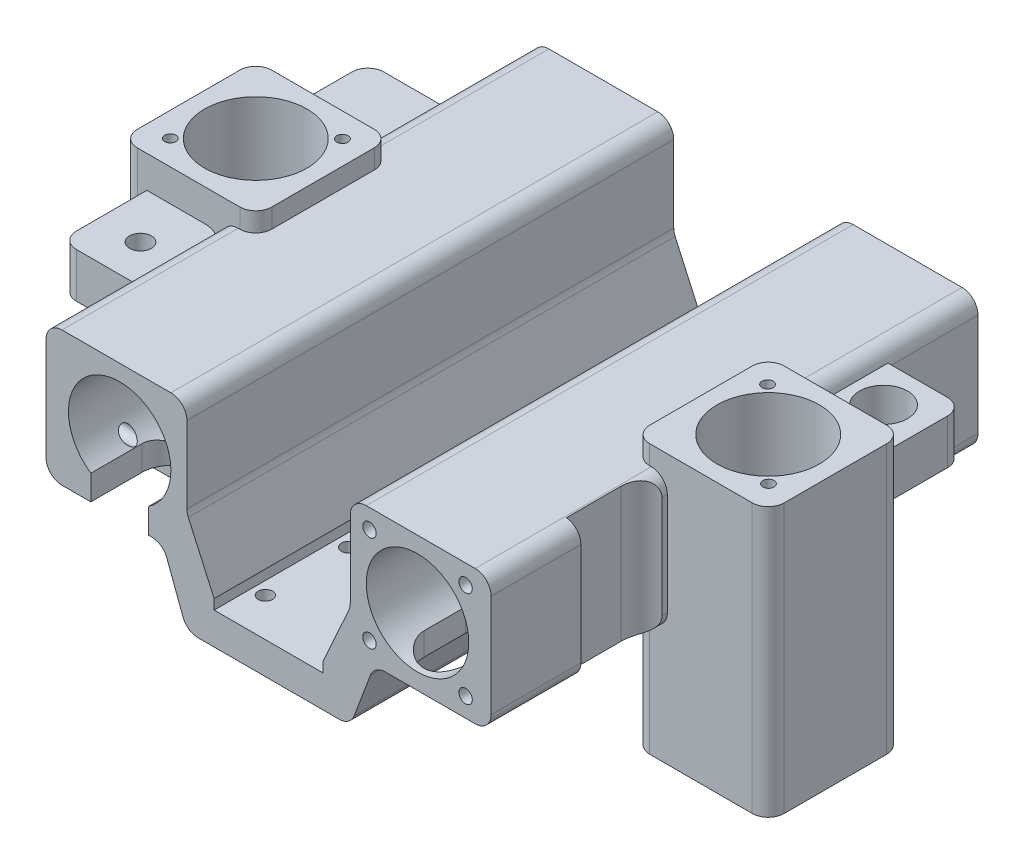
SolidWorks part; units mm, degrees
ref_plane "前视基准面" through (0, 0, 0) normal (0, 0, 1) x (1, 0, 0)
ref_plane "上视基准面" through (0, 0, 0) normal (0, 1, 0) x (1, 0, 0)
ref_plane "右视基准面" through (0, 0, 0) normal (1, 0, 0) x (0, 0, -1)
sketch "草图1" plane through (0, 0, 0) normal (0, 0, 1) x (1, 0, 0)
  line L453 (2723.1468, 1081.2034) -> (2758.5766, 1081.2034) construction
  line L454 (2741.2781, 1063.9052) -> (2741.2781, 1099.5334) construction
  line L455 (2648.2781, 1065.0579) -> (2648.2781, 1099.5334) construction
  line L456 (2631.7099, 1081.2034) -> (2665.5766, 1081.2034) construction
  line L472 (2731.2431, 1060.2034) -> (2759.2781, 1060.2034)
  line L473 (2725.2781, 1102.2034) -> (2759.2781, 1102.2034)
  line L474 (2669.2781, 1073.2765) -> (2669.2781, 1097.2034)
  line L475 (2720.2781, 1073.2765) -> (2720.2781, 1097.2034)
  line L476 (2677.7781, 1053.3145) -> (2669.7185, 1071.2247)
  line L477 (2711.7781, 1053.3145) -> (2719.8377, 1071.2247)
  line L478 (2721.4948, 1043.4478) -> (2726.5615, 1056.959)
  line L479 (2668.0615, 1043.4478) -> (2662.9948, 1056.959)
  line L480 (2694.7781, 1009.1509) -> (2694.7781, 1126.7648) construction
  line L483 (2764.2781, 1065.2034) -> (2764.2781, 1097.2034)
  line L484 (2625.2781, 1065.2034) -> (2625.2781, 1097.2034)
  line L485 (2677.7781, 1050.2034) -> (2711.7781, 1050.2034)
  line L486 (2711.7781, 1050.2034) -> (2711.7781, 1053.3145)
  line L487 (2677.7781, 1050.2034) -> (2677.7781, 1053.3145)
  line L488 (2672.7431, 1040.2034) -> (2716.8131, 1040.2034)
  line L491 (2630.2781, 1060.2034) -> (2658.3131, 1060.2034)
  line L492 (2630.2781, 1102.2034) -> (2664.2781, 1102.2034)
  circle A141 centre (2648.2781, 1081.2034) radius 14
  circle A142 centre (2741.2781, 1081.2034) radius 16
  arc A143 (2759.2781, 1060.2034) -> (2764.2781, 1065.2034) centre (2759.2781, 1065.2034) ccw
  arc A144 (2731.2431, 1060.2034) -> (2726.5615, 1056.959) centre (2731.2431, 1055.2034) ccw
  arc A145 (2764.2781, 1097.2034) -> (2759.2781, 1102.2034) centre (2759.2781, 1097.2034) ccw
  arc A146 (2725.2781, 1102.2034) -> (2720.2781, 1097.2034) centre (2725.2781, 1097.2034) ccw
  arc A147 (2669.2781, 1073.2765) -> (2669.7185, 1071.2247) centre (2674.2781, 1073.2765) ccw
  arc A148 (2719.8377, 1071.2247) -> (2720.2781, 1073.2765) centre (2715.2781, 1073.2765) ccw
  arc A149 (2716.8131, 1040.2034) -> (2721.4948, 1043.4478) centre (2716.8131, 1045.2034) ccw
  arc A150 (2668.0615, 1043.4478) -> (2672.7431, 1040.2034) centre (2672.7431, 1045.2034) ccw
  arc A151 (2625.2781, 1065.2034) -> (2630.2781, 1060.2034) centre (2630.2781, 1065.2034) ccw
  arc A152 (2662.9948, 1056.959) -> (2658.3131, 1060.2034) centre (2658.3131, 1055.2034) ccw
  arc A153 (2630.2781, 1102.2034) -> (2625.2781, 1097.2034) centre (2630.2781, 1097.2034) ccw
  arc A154 (2669.2781, 1097.2034) -> (2664.2781, 1102.2034) centre (2664.2781, 1097.2034) ccw
extrude "拉伸1" add sketch "草图1" along normal blind 152
ref_plane "基准面2" through (0, 1108.2034, 0) normal (0, 1, 0) x (-1, 0, 0)
sketch "草图3" plane through (0, 1108.2034, 0) normal (0, 1, 0) x (-1, 0, 0)
  line L0 (-2694.7781, 0) -> (-2694.7781, 152) construction
  line L1 (-2598.7781, 55) -> (-2630.7781, 55)
  line L2 (-2593.7781, 60) -> (-2593.7781, 92)
  line L3 (-2598.7781, 97) -> (-2630.7781, 97)
  line L4 (-2635.7781, 60) -> (-2635.7781, 92)
  line L5 (-2711.7781, 0) -> (-2677.7781, 0) construction
  line L6 (-2711.7781, 152) -> (-2677.7781, 152) construction
  line L7 (-2664.2781, 0) -> (-2630.2781, 0) construction
  line L8 (-2790.7781, 97) -> (-2758.7781, 97)
  line L9 (-2753.7781, 60) -> (-2753.7781, 92)
  line L10 (-2790.7781, 55) -> (-2758.7781, 55)
  line L11 (-2795.7781, 60) -> (-2795.7781, 92)
  arc A0 (-2593.7781, 60) -> (-2598.7781, 55) centre (-2598.7781, 60) cw
  arc A1 (-2635.7781, 60) -> (-2630.7781, 55) centre (-2630.7781, 60) ccw
  arc A2 (-2598.7781, 97) -> (-2593.7781, 92) centre (-2598.7781, 92) cw
  arc A3 (-2635.7781, 92) -> (-2630.7781, 97) centre (-2630.7781, 92) cw
  circle A4 centre (-2614.7781, 76) radius 16
  arc A5 (-2790.7781, 97) -> (-2795.7781, 92) centre (-2790.7781, 92) ccw
  arc A6 (-2753.7781, 92) -> (-2758.7781, 97) centre (-2758.7781, 92) ccw
  arc A7 (-2753.7781, 60) -> (-2758.7781, 55) centre (-2758.7781, 60) cw
  circle A8 centre (-2774.7781, 76) radius 16
  arc A9 (-2795.7781, 60) -> (-2790.7781, 55) centre (-2790.7781, 60) ccw
  point P6 (-2593.7781, 55)
  point P9 (-2635.7781, 55)
  point P12 (-2593.7781, 97)
  dimension "D3" = 5
  dimension "D6" = 32
  dimension "D7" = 21
  dimension "D8" = 21
  dimension "D1" = 42
  dimension "D2" = 42
  dimension "D4" = 59
  dimension "D5" = 55
extrude "拉伸2" add sketch "草图3" against normal blind 84
sketch "草图4" plane through (0, 1108.2034, 0) normal (0, 1, 0) x (-1, 0, 0)
  line L0 (-2694.7781, 0) -> (-1335.5398, -1233.902) construction
  line L1 (-2711.7781, 0) -> (-2677.7781, 0) construction
  line L2 (-2694.7781, 151.4457) -> (-2694.7781, 0) construction
  circle A0 centre (-2601.3905, 89.2999) radius 1.75
  circle A1 centre (-2628.4032, 62.5732) radius 1.75
  arc A4 (-2635.7781, 60) -> (-2630.7781, 55) centre (-2630.7781, 60) ccw construction
  circle A7 centre (-2761.153, 62.5732) radius 1.75
  circle A8 centre (-2788.1657, 89.2999) radius 1.75
  point P5 (-2634.3137, 56.4645)
  dimension "D1" = 38
  dimension "D3" = 3.5
  dimension "D4" = 3.5
  dimension "D2" = 8.5
extrude "拉伸3" cut sketch "草图4" against normal blind 15
sketch "草图5" plane through (0, 1024.2034, 0) normal (0, -1, 0) x (1, 0, 0)
  circle A0 centre (2601.3905, 89.2999) radius 1.75
  circle A1 centre (2628.4032, 62.5732) radius 1.75
  circle A2 centre (2788.1657, 89.2999) radius 1.7851
  circle A3 centre (2761.153, 62.5732) radius 1.75
extrude "拉伸4" cut sketch "草图5" against normal blind 15
ref_plane "基准面3" through (0, 1084.2034, 0) normal (0, 1, 0) x (-1, 0, 0)
sketch "草图6" plane through (0, 1084.2034, 0) normal (0, 1, 0) x (-1, 0, 0)
  line L0 (-2606.7781, 28) -> (-2629.7781, 28)
  line L1 (-2629.7781, 28) -> (-2629.7781, 45)
  line L2 (-2630.7781, 55) -> (-2598.7781, 55) construction
  line L3 (-2635.7781, 92) -> (-2635.7781, 60) construction
  line L4 (-2601.7781, 33) -> (-2601.7781, 52.5097)
  line L5 (-2601.7781, 52.5097) -> (-2601.7781, 55)
  line L6 (-2601.7781, 55) -> (-2619.7781, 55)
  line L7 (-2694.7781, 0) -> (-2694.7781, 152) construction
  line L8 (-2711.7781, 0) -> (-2677.7781, 0) construction
  line L9 (-2711.7781, 152) -> (-2677.7781, 152) construction
  line L10 (-2764.2781, 76) -> (-2625.2781, 76) construction
  line L11 (-2764.2781, 88.0727) -> (-2764.2781, 63.9273) construction
  line L12 (-2625.2781, 88.0727) -> (-2625.2781, 63.9273) construction
  line L13 (-2787.7781, 55) -> (-2769.7781, 55)
  line L14 (-2787.7781, 52.5097) -> (-2787.7781, 55)
  line L15 (-2787.7781, 33) -> (-2787.7781, 52.5097)
  line L16 (-2759.7781, 28) -> (-2759.7781, 45)
  line L17 (-2782.7781, 28) -> (-2759.7781, 28)
  line L19 (-2759.7781, 124) -> (-2759.7781, 107)
  line L22 (-2787.7781, 97) -> (-2769.7781, 97)
  line L23 (-2601.7781, 97) -> (-2619.7781, 97)
  line L24 (-2601.7781, 99.4903) -> (-2601.7781, 97)
  line L25 (-2601.7781, 119) -> (-2601.7781, 99.4903)
  line L26 (-2629.7781, 124) -> (-2629.7781, 107)
  line L27 (-2606.7781, 124) -> (-2629.7781, 124)
  line L28 (-2759.7781, 124) -> (-2782.7781, 124)
  line L29 (-2787.7781, 119) -> (-2787.7781, 97)
  arc A0 (-2601.7781, 33) -> (-2606.7781, 28) centre (-2606.7781, 33) cw
  arc A1 (-2619.7781, 55) -> (-2629.7781, 45) centre (-2619.7781, 45) ccw
  circle A2 centre (-2774.7781, 40) radius 7.5
  circle A3 centre (-2774.7781, 76) radius 16 construction
  arc A4 (-2787.7781, 33) -> (-2782.7781, 28) centre (-2782.7781, 33) ccw
  arc A6 (-2787.7781, 119) -> (-2782.7781, 124) centre (-2782.7781, 119) cw
  arc A7 (-2769.7781, 97) -> (-2759.7781, 107) centre (-2769.7781, 107) ccw
  circle A10 centre (-2614.7781, 76) radius 16 construction
  arc A11 (-2619.7781, 97) -> (-2629.7781, 107) centre (-2619.7781, 107) cw
  arc A12 (-2601.7781, 119) -> (-2606.7781, 124) centre (-2606.7781, 119) ccw
  circle A13 centre (-2614.7781, 112) radius 3.4
  arc A22 (-2769.7781, 55) -> (-2759.7781, 45) centre (-2769.7781, 45) cw
  dimension "D4" = 5
  dimension "D5" = 10
  dimension "D9" = 15
  dimension "D10" = 36
  dimension "D11" = 6.8
  dimension "D12" = 36
  dimension "D13" = 0
  dimension "D1" = 27
  dimension "D2" = 6
  dimension "D3" = 28
extrude "拉伸5" add sketch "草图6" along normal blind 14
sketch "草图7" plane through (0, 1060.2034, 0) normal (0, -1, 0) x (1, 0, 0)
  line L0 (2694.7781, 152) -> (2694.7781, 0) construction
  line L1 (2672.7431, 152) -> (2716.8131, 152) construction
  line L2 (2672.7431, 0) -> (2716.8131, 0) construction
  line L3 (2639.2781, 152) -> (2639.2781, 136)
  line L4 (2648.2781, 141.8186) -> (2648.2781, 166.4438) construction
  line L5 (2657.2781, 136) -> (2657.2781, 152)
  line L6 (2657.2781, 152) -> (2639.2781, 152)
  line L7 (2630.2781, 152) -> (2658.3131, 152) construction
  line L8 (2764.2781, 76) -> (2625.2781, 76) construction
  line L9 (2764.2781, 88.0727) -> (2764.2781, 63.9273) construction
  line L10 (2625.2781, 88.0727) -> (2625.2781, 63.9273) construction
  line L11 (2657.2781, 0) -> (2639.2781, 0)
  line L12 (2657.2781, 16) -> (2657.2781, 0)
  line L13 (2639.2781, 0) -> (2639.2781, 16)
  line L14 (2741.2781, 161.8728) -> (2741.2781, 126.2694) construction
  line L15 (2749.2781, 142) -> (2749.2781, 129)
  line L16 (2741.2781, -9.8728) -> (2741.2781, 25.7306) construction
  line L17 (2733.2781, 129) -> (2733.2781, 142)
  line L18 (2733.2781, 23) -> (2733.2781, 10)
  line L20 (2749.2781, 10) -> (2749.2781, 23)
  arc A0 (2639.2781, 136) -> (2657.2781, 136) centre (2648.2781, 136) ccw
  arc A1 (2639.2781, 16) -> (2657.2781, 16) centre (2648.2781, 16) cw
  arc A2 (2733.2781, 129) -> (2749.2781, 129) centre (2741.2781, 129) ccw
  arc A3 (2749.2781, 142) -> (2733.2781, 142) centre (2741.2781, 142) ccw
  arc A4 (2749.2781, 10) -> (2733.2781, 10) centre (2741.2781, 10) cw
  arc A5 (2733.2781, 23) -> (2749.2781, 23) centre (2741.2781, 23) cw
  dimension "D2" = 9
  dimension "D1" = 46.5
  dimension "D3" = 18
  dimension "D4" = 16
  dimension "D5" = 16
  dimension "D6" = 0
  dimension "D7" = 46.5
  dimension "D8" = 13
  dimension "D9" = 16
  dimension "D10" = 8
extrude "拉伸6" cut sketch "草图7" against normal up to next
sketch "草图9" plane through (0, 1040.2034, 0) normal (0, -1, 0) x (1, 0, 0)
  line L0 (2694.7781, 152) -> (2694.7781, 0) construction
  line L1 (2672.7431, 152) -> (2716.8131, 152) construction
  line L2 (2672.7431, 0) -> (2716.8131, 0) construction
  circle A0 centre (2681.7781, 140) radius 2.25
  circle A1 centre (2707.7781, 140) radius 2.25
  circle A2 centre (2681.7781, 114) radius 2.25
  circle A3 centre (2707.7781, 114) radius 2.25
  dimension "D1" = 4.5
  dimension "D2" = 4.5
  dimension "D3" = 4.5
  dimension "D4" = 4.5
  dimension "D5" = 26
  dimension "D6" = 26
  dimension "D7" = 26
  dimension "D9" = 12
  dimension "D8" = 13
extrude "拉伸7" cut sketch "草图9" against normal through all
sketch "草图10" plane through (0, 1040.2034, 0) normal (0, -1, 0) x (1, 0, 0)
  circle A0 centre (2681.7781, 140) radius 4.25
  circle A1 centre (2707.7781, 140) radius 4.25
  circle A2 centre (2707.7781, 114) radius 4.25
  circle A3 centre (2681.7781, 114) radius 4.25
  dimension "D1" = 8.5
  dimension "D2" = 8.5
  dimension "D3" = 8.5
  dimension "D4" = 8.5
extrude "拉伸8" cut sketch "草图10" against normal blind 5
ref_plane "基准面4" through (0, 0, 76) normal (0, 0, 1) x (1, 0, 0)
mirror "镜向1" about plane through (0, 0, 76) normal (0, 0, 1) of "拉伸7", "拉伸8"
sketch "草图12" plane through (2625.2781, 0, 0) normal (-1, 0, 0) x (0, 0, 1)
  line L0 (152, 1102.2034) -> (97, 1102.2034) construction
  line L1 (152, 1097.2034) -> (152, 1065.2034) construction
  circle A0 centre (138, 1092.2034) radius 2.1
  circle A1 centre (138, 1070.2034) radius 2.1
  dimension "D1" = 4.2
  dimension "D2" = 4.2
  dimension "D3" = 22
  dimension "D4" = 10
  dimension "D5" = 14
extrude "拉伸9" cut sketch "草图12" against normal up to next
sketch "草图13" plane through (0, 1084.2034, 0) normal (0, -1, 0) x (1, 0, 0)
  line L0 (2759.7781, 124) -> (2759.7781, 107)
  line L1 (2795.7781, 92) -> (2795.7781, 60) construction
  line L2 (2787.7781, 97) -> (2769.7781, 97)
  line L4 (2759.7781, 124) -> (2782.7781, 124)
  line L5 (2787.7781, 119) -> (2787.7781, 97)
  arc A0 (2782.7781, 124) -> (2787.7781, 119) centre (2782.7781, 119) cw
  arc A1 (2759.7781, 107) -> (2769.7781, 97) centre (2769.7781, 107) ccw
  dimension "D2" = 10
  dimension "D1" = 36
extrude "拉伸11" cut sketch "草图13" against normal mid plane 100
sketch "草图14" plane through (0, 1024.2034, 0) normal (0, -1, 0) x (1, 0, 0)
  circle A0 centre (2614.7781, 76) radius 16
  circle A1 centre (2774.7781, 76) radius 16
extrude "拉伸12" cut sketch "草图14" against normal through all
sketch "草图15" plane through (0, 0, 152) normal (0, 0, 1) x (1, 0, 0)
  circle A0 centre (2648.2781, 1081.2034) radius 16
  circle A2 centre (2741.2781, 1081.2034) radius 16
  dimension "D1" = 32
  dimension "D2" = 32
extrude "拉伸13" cut sketch "草图15" against normal through all
sketch "草图16" plane through (0, 0, 0) normal (0, 0, -1) x (-1, 0, 0)
  line L0 (-2741.2781, 1081.2034) -> (-2749.7034, 1081.2034) construction
  line L1 (-2741.2781, 1081.2034) -> (-2741.2781, 1087.115) construction
  circle A0 centre (-2756.2781, 1096.2034) radius 2.1
  circle A1 centre (-2726.2781, 1096.2034) radius 2.1
  circle A2 centre (-2726.2781, 1066.2034) radius 2.1
  circle A3 centre (-2756.2781, 1066.2034) radius 2.1
  dimension "D1" = 4.2
  dimension "D2" = 15
  dimension "D3" = 30
extrude "拉伸14" cut sketch "草图16" against normal blind 15
mirror "镜向3" about plane through (0, 0, 76) normal (0, 0, 1) of "拉伸14"
hole_wizard "M5 螺纹孔1" positions "草图18" profile "草图17" tap size "M5" standard "ISO"
sketch "草图18" plane through (2625.2781, 0, 0) normal (-1, 0, 0) x (0, 0, 1)
  line L0 (0, 1097.2034) -> (0, 1065.2034) construction
  line L1 (55, 1102.2034) -> (0, 1102.2034) construction
  point P0 (17, 1070.2034)
  point P1 (17, 1092.2034)
  dimension "D1" = 17
  dimension "D2" = 10
  dimension "D3" = 22
sketch "草图17" plane through (2625.2781, 1070.2034, 17) normal (0, 1, 0) x (0, 0, 1)
  line L0 (0, 0) -> (0, 13.6618)
  line L1 (0, 13.6618) -> (2.1, 12.4)
  line L2 (2.1, 12.4) -> (2.1, 0)
  line L5 (2.1, 0) -> (0, 0)
  line L10 (0, 13.6618) -> (-2.1, 12.4) construction
  line L11 (0, -6.35) -> (0, 107.95) construction
  dimension "螺纹孔钻头直径" = 4.2
  dimension "螺纹孔钻头深度" = 12.4
  dimension "导头角度" = 118
cosmetic thread "孔螺蚊线1" parameters "D1"=10, "D2"=5
cosmetic thread "孔螺蚊线2" parameters "D1"=10, "D2"=5
